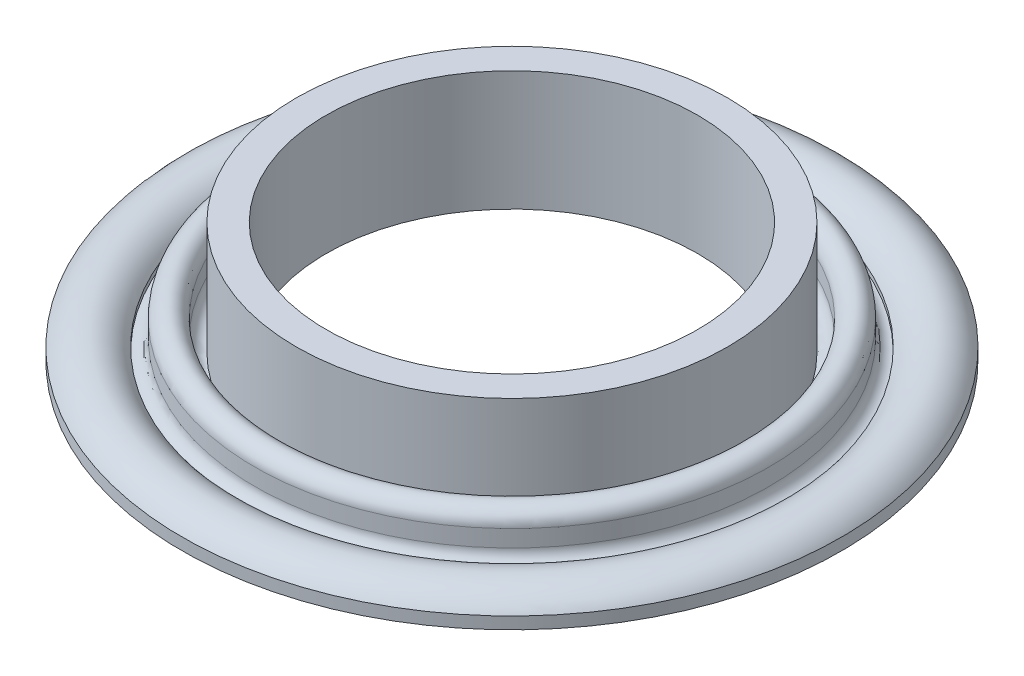
SolidWorks part; units mm, degrees
ref_plane "Front Plane" through (0, 0, 0) normal (0, 0, 1) x (1, 0, 0)
ref_plane "Top Plane" through (0, 0, 0) normal (0, 1, 0) x (1, 0, 0)
ref_plane "Right Plane" through (0, 0, 0) normal (1, 0, 0) x (0, 0, -1)
sketch "Sketch1" plane through (0, 0, 0) normal (0, 0, 1) x (1, 0, 0)
  line L0 (0, 0) -> (0, 28.2317) construction
  line L1 (0, 0) -> (69.85, 0) construction
  line L2 (57.15, 0) -> (69.85, 0)
  line L3 (57.15, 1.524) -> (57.15, 2.54)
  line L4 (69.85, 0) -> (69.85, 2.54)
  line L5 (39.37, 0) -> (39.37, 25.4)
  line L6 (39.37, 25.4) -> (45.72, 25.4)
  line L7 (45.72, 25.4) -> (45.72, 1.524)
  line L8 (45.72, 0) -> (39.37, 0)
  line L9 (49.889, 4.169) -> (49.889, 7.7341)
  line L10 (52.981, 7.7341) -> (52.981, 4.169)
  line L11 (48.365, 4.169) -> (48.365, 7.7341)
  line L12 (54.505, 7.7341) -> (54.505, 4.169)
  arc A1 (57.15, 2.54) -> (69.85, 2.54) centre (63.5, -1.6721) cw
  arc A2 (45.72, 0) -> (49.889, 4.169) centre (45.72, 4.169) ccw
  arc A3 (57.15, 0) -> (52.981, 4.169) centre (57.15, 4.169) cw
  arc A4 (49.889, 7.7341) -> (52.981, 7.7341) centre (51.435, 7.7341) cw
  arc A5 (45.72, 1.524) -> (48.365, 4.169) centre (45.72, 4.169) ccw
  arc A6 (48.365, 7.7341) -> (54.505, 7.7341) centre (51.435, 7.7341) cw
  arc A7 (57.15, 1.524) -> (54.505, 4.169) centre (57.15, 4.169) cw
  dimension "D1" = 114.3
  dimension "D3" = 2.54
  dimension "D4" = 7.62
  dimension "D8" = 7.7341
  dimension "D9" = 1.524
  dimension "D2" = 12.7
  dimension "D5" = 78.74
  dimension "D6" = 6.35
  dimension "D7" = 25.4
  dimension "D10" = 4.169
revolve "Revolve1" add sketch "Sketch1" angle 360 about L0
